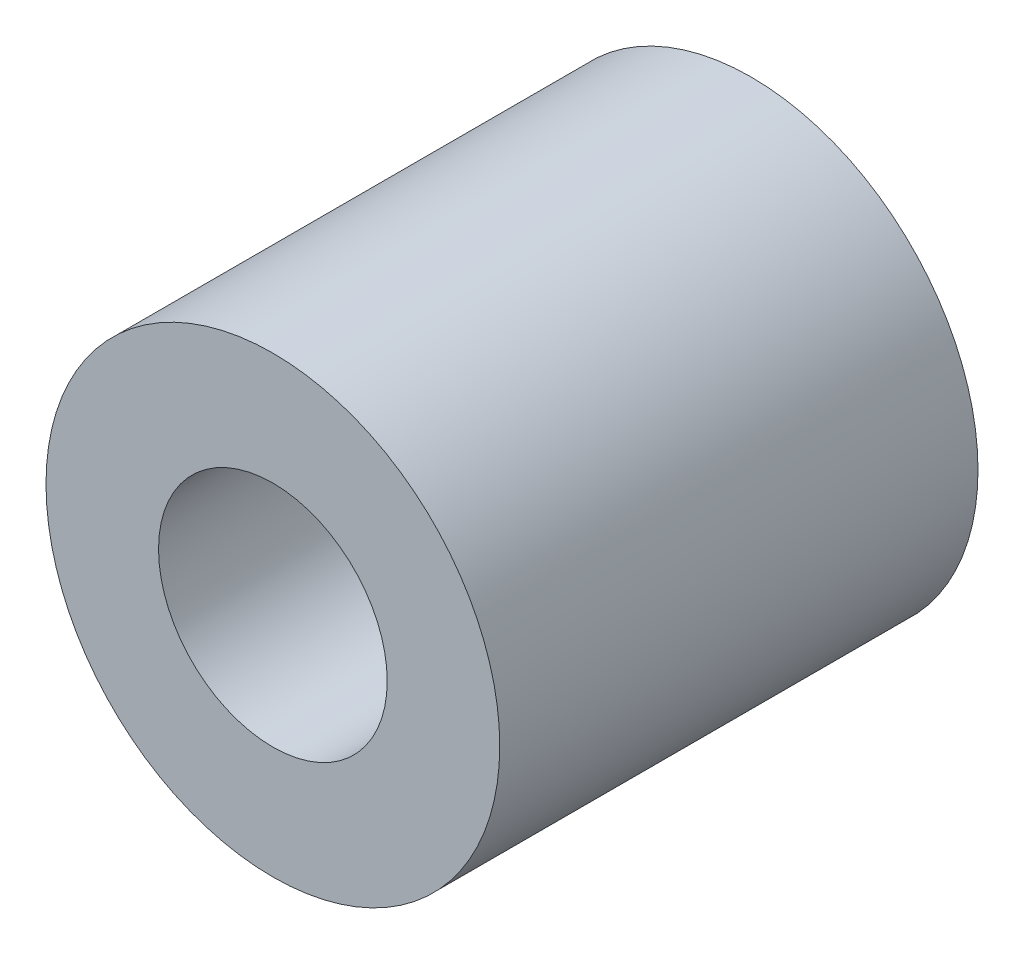
SolidWorks part; units mm, degrees
ref_plane "Front Plane" through (0, 0, 0) normal (0, 0, 1) x (1, 0, 0)
ref_plane "Top Plane" through (0, 0, 0) normal (0, 1, 0) x (1, 0, 0)
ref_plane "Right Plane" through (0, 0, 0) normal (1, 0, 0) x (0, 0, -1)
sketch "Sketch1" plane through (0, 0, 0) normal (0, 0, 1) x (1, 0, 0)
  circle A0 centre (0, 0) radius 6.35
  circle A1 centre (0, 0) radius 3.2004
  dimension "OD" = 12.7
  dimension "ID" = 6.4008
extrude "Extrude1" add sketch "Sketch1" along normal mid plane 13.3858
sketch "Sketch2" plane through (0, 0, 0) normal (1, 0, 0) x (0, 0, -1)
  line L0 (-6.6929, -3.2004) -> (6.6929, -3.2004) construction
  line L3 (6.6929, 3.2004) -> (-6.6929, 3.2004) construction
  line L5 (-6.6929, -3.2004) -> (6.6929, -3.2004)
  line L6 (6.6929, 3.2004) -> (-6.6929, 3.2004)
sketch "Sketch4" plane through (0, 0, 6.6929) normal (0, 0, 1) x (1, 0, 0)
  line L0 (0, 0) -> (-2.263, 2.263)
  line L1 (0, -55) -> (0, 55) construction
  circle A0 centre (0, 0) radius 3.2004 construction
  dimension "D1" = 45
